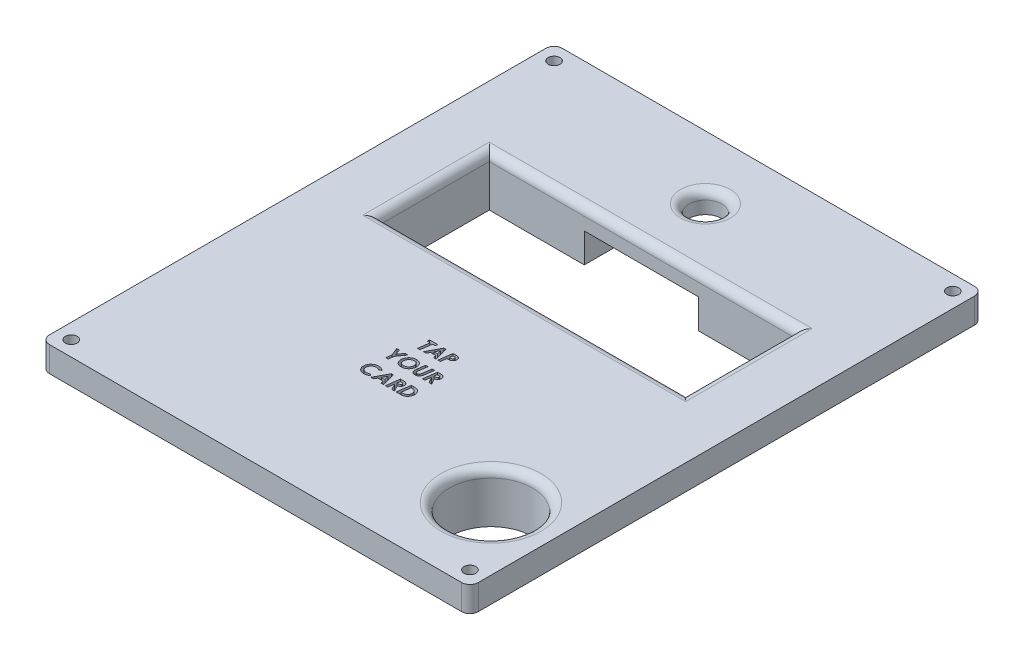
SolidWorks part; units mm, degrees
ref_plane "Front Plane" through (0, 0, 0) normal (0, 0, 1) x (1, 0, 0)
ref_plane "Top Plane" through (0, 0, 0) normal (0, 1, 0) x (1, 0, 0)
ref_plane "Right Plane" through (0, 0, 0) normal (1, 0, 0) x (0, 0, -1)
sketch "Sketch2" plane through (0, 0, 0) normal (0, 1, 0) x (1, 0, 0)
  line L1 (-88, 110) -> (-2, 110)
  line L2 (-90, 108) -> (-90, 2)
  line L3 (-88, 0) -> (-2, 0)
  line L4 (0, 108) -> (0, 2)
  line L5 (-94, 116) -> (4, 116)
  line L6 (-96, 114) -> (-96, -4)
  line L7 (-94, -6) -> (4, -6)
  line L8 (6, 114) -> (6, -4)
  arc A0 (-88, 0) -> (-90, 2) centre (-88, 2) cw
  arc A1 (0, 2) -> (-2, 0) centre (-2, 2) cw
  arc A2 (-2, 110) -> (0, 108) centre (-2, 108) cw
  arc A3 (-88, 110) -> (-90, 108) centre (-88, 108) ccw
  arc A4 (-94, 116) -> (-96, 114) centre (-94, 114) ccw
  arc A5 (4, 116) -> (6, 114) centre (4, 114) cw
  arc A6 (4, -6) -> (6, -4) centre (4, -4) ccw
  arc A7 (-96, -4) -> (-94, -6) centre (-94, -4) ccw
  point P7 (-90, 0)
  point P10 (0, 0)
  point P13 (0, 110)
  point P16 (-90, 110)
  dimension "D3" = 2
  dimension "D8" = 2
  dimension "D1" = 90
  dimension "D2" = 110
  dimension "D4" = 6
  dimension "D5" = 6
  dimension "D6" = 6
  dimension "D7" = 6
extrude "Boss-Extrude1" add sketch "Sketch2" along normal blind 6
sketch "Sketch3" plane through (0, 6, 0) normal (0, 1, 0) x (1, 0, 0)
  line L0 (-95.4142, 115.4142) -> (-89.4142, 109.4142) construction
  arc A0 (-94, 116) -> (-96, 114) centre (-94, 114) ccw construction
  arc A1 (-88, 110) -> (-90, 108) centre (-88, 108) ccw construction
  circle A2 centre (-92.4142, 112.4142) radius 1.4
  dimension "D1" = 2.8
extrude "Cut-Extrude1" cut sketch "Sketch3" against normal through all
ref_plane "Plane1" through (-45, 0, 0) normal (-1, 0, 0) x (0, 0, 1)
mirror "Mirror1" about plane through (-45, 0, 0) normal (-1, 0, 0) of "Cut-Extrude1"
ref_plane "Plane2" through (0, 0, -55) normal (0, 0, 1) x (1, 0, 0)
mirror "Mirror2" about plane through (0, 0, -55) normal (0, 0, 1) of "Mirror1", "Cut-Extrude1"
sketch "Sketch4" plane through (0, 6, 0) normal (0, 1, 0) x (1, 0, 0)
  line L0 (-88, 0) -> (-2, 0) construction
  line L1 (0, 2) -> (0, 108) construction
  line L2 (-2, 110) -> (-88, 110) construction
  line L3 (-90, 108) -> (-90, 2) construction
  line L12 (-88, 0) -> (-2, 0)
  line L13 (0, 2) -> (0, 108)
  line L14 (-2, 110) -> (-88, 110)
  line L15 (-90, 108) -> (-90, 2)
  arc A0 (-90, 2) -> (-88, 0) centre (-88, 2) ccw construction
  arc A1 (-2, 0) -> (0, 2) centre (-2, 2) ccw construction
  arc A2 (0, 108) -> (-2, 110) centre (-2, 108) ccw construction
  arc A3 (-88, 110) -> (-90, 108) centre (-88, 108) ccw construction
  arc A12 (-90, 2) -> (-88, 0) centre (-88, 2) ccw
  arc A13 (-2, 0) -> (0, 2) centre (-2, 2) ccw
  arc A14 (0, 108) -> (-2, 110) centre (-2, 108) ccw
  arc A15 (-88, 110) -> (-90, 108) centre (-88, 108) ccw
extrude "Boss-Extrude2" add sketch "Sketch4" against normal blind 12
sketch "Sketch5" plane through (0, 6, 0) normal (0, 1, 0) x (1, 0, 0)
  line L1 (-81.4, 86) -> (-8.6, 86)
  line L2 (-81.4, 86) -> (-81.4, 59.9)
  line L3 (-81.4, 59.9) -> (-8.6, 59.9)
  line L4 (-8.6, 86) -> (-8.6, 59.9)
  line L8 (4, 116) -> (-94, 116) construction
  line L9 (-45, 86) -> (-45, 101) construction
  line L13 (6, -4) -> (6, 114) construction
  line L15 (-96, 114) -> (-96, -4) construction
  circle A0 centre (-45, 101) radius 3.9
  dimension "D5" = 7.8
  dimension "D1" = 72.8
  dimension "D2" = 14.6
  dimension "D3" = 26.1
  dimension "D4" = 30
  dimension "D6" = 15
  dimension "D7" = 51
extrude "Cut-Extrude2" cut sketch "Sketch5" against normal blind 12
fillet "Fillet1" radius 2 5 edges at (-45, 6, -59.9) (-8.6, 6, -72.95) (-45, 6, -86) (-81.4, 6, -72.95) (-45, 6, -97.1)
sketch "Sketch6" plane through (0, -6, 0) normal (0, -1, 0) x (1, 0, 0)
  line L0 (-81.4, -59.9) -> (-8.6, -59.9) construction
  line L1 (-29.95, -54.9) -> (-69.25, -54.9)
  line L2 (-29.95, -54.9) -> (-29.95, 4.8)
  line L3 (-29.95, 4.8) -> (-69.25, 4.8)
  line L4 (-69.25, -54.9) -> (-69.25, 4.8)
  line L5 (-90, -108) -> (-90, -2) construction
  dimension "D1" = 59.7
  dimension "D2" = 5
  dimension "D3" = 39.3
  dimension "D4" = 20.75
extrude "Cut-Extrude3" cut sketch "Sketch6" against normal blind 10
sketch "Sketch7" plane through (0, 6, 0) normal (0, 1, 0) x (1, 0, 0)
  line L0 (-81, 36.9928) -> (-11, 36.9928) construction
  line L6 (-81, 31.3014) -> (-11, 31.3014) construction
  line L7 (-81, 25.4641) -> (-11, 25.4641) construction
  line L8 (-96, 114) -> (-96, -4) construction
  text T0 "<b><i>TAP</i></b>"
  text T1 "<b><i>YOUR</i></b>"
  text T2 "<b><i>CARD</i></b>"
  dimension "D1" = 15
  dimension "D2" = 15
  dimension "D3" = 15
extrude "Cut-Extrude4" cut sketch "Sketch7" against normal blind 2
sketch "Sketch8" plane through (0, 6, 0) normal (0, 1, 0) x (1, 0, 0)
  line L0 (6, -4) -> (6, 114) construction
  line L1 (-94, -6) -> (4, -6) construction
  circle A0 centre (-9, 14) radius 9.9
  dimension "D1" = 19.8
  dimension "D2" = 15
  dimension "D3" = 20
extrude "Cut-Extrude5" cut sketch "Sketch8" against normal through all
fillet "Fillet2" radius 2 1 edges at (-9, 6, -4.1)
sketch "Sketch10" plane through (0, -6, 0) normal (0, -1, 0) x (1, 0, 0)
  line L0 (-2, -110) -> (-88, -110) construction
  line L1 (-31.6, -110) -> (-58.8, -110)
  line L2 (-31.6, -110) -> (-31.6, -86)
  line L3 (-31.6, -86) -> (-58.8, -86)
  line L4 (-58.8, -110) -> (-58.8, -86)
  line L5 (-8.6, -86) -> (-81.4, -86) construction
  line L6 (0, -18.1243) -> (0, -108) construction
  dimension "D1" = 27.2
  dimension "D2" = 31.6
extrude "Cut-Extrude6" cut sketch "Sketch10" against normal blind 7
